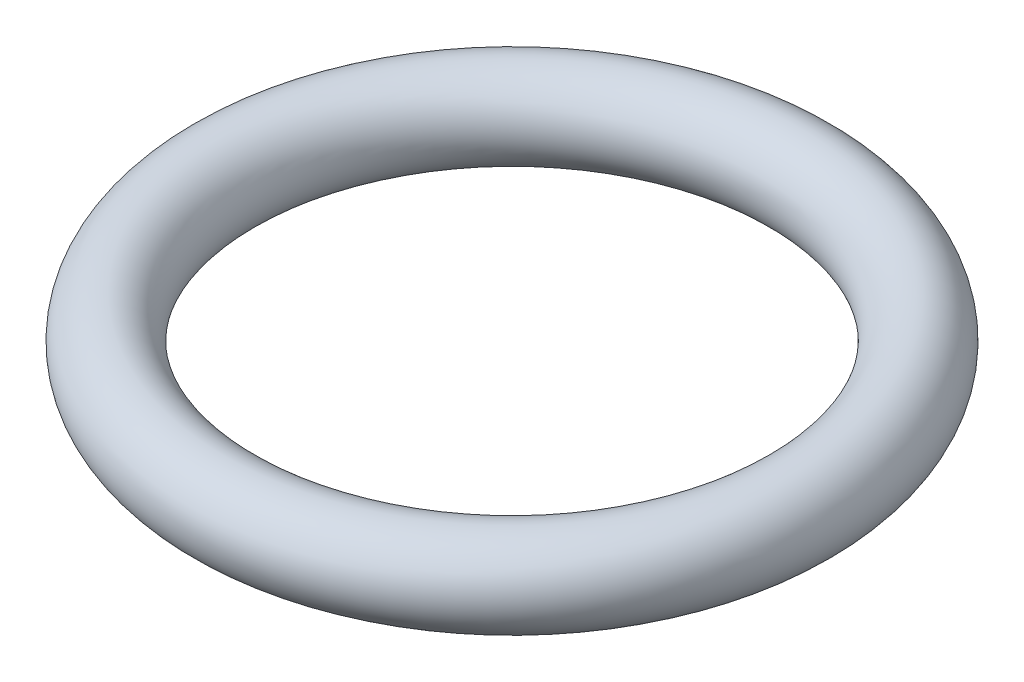
SolidWorks part; units mm, degrees
ref_plane "Front Plane" through (0, 0, 0) normal (0, 0, 1) x (1, 0, 0)
ref_plane "Top Plane" through (0, 0, 0) normal (0, 1, 0) x (1, 0, 0)
ref_plane "Right Plane" through (0, 0, 0) normal (1, 0, 0) x (0, 0, -1)
sketch "Sketch1" plane through (0, 0, 0) normal (0, 0, 1) x (1, 0, 0)
  line L0 (0, -146.1287) -> (0, 7160.3059) construction
  circle A0 centre (5.3848, 0) radius 0.7938
  dimension "D2" = 1.5875
  dimension "D1" = 5.3848
revolve "Revolve1" add sketch "Sketch1" angle 360 about L0
